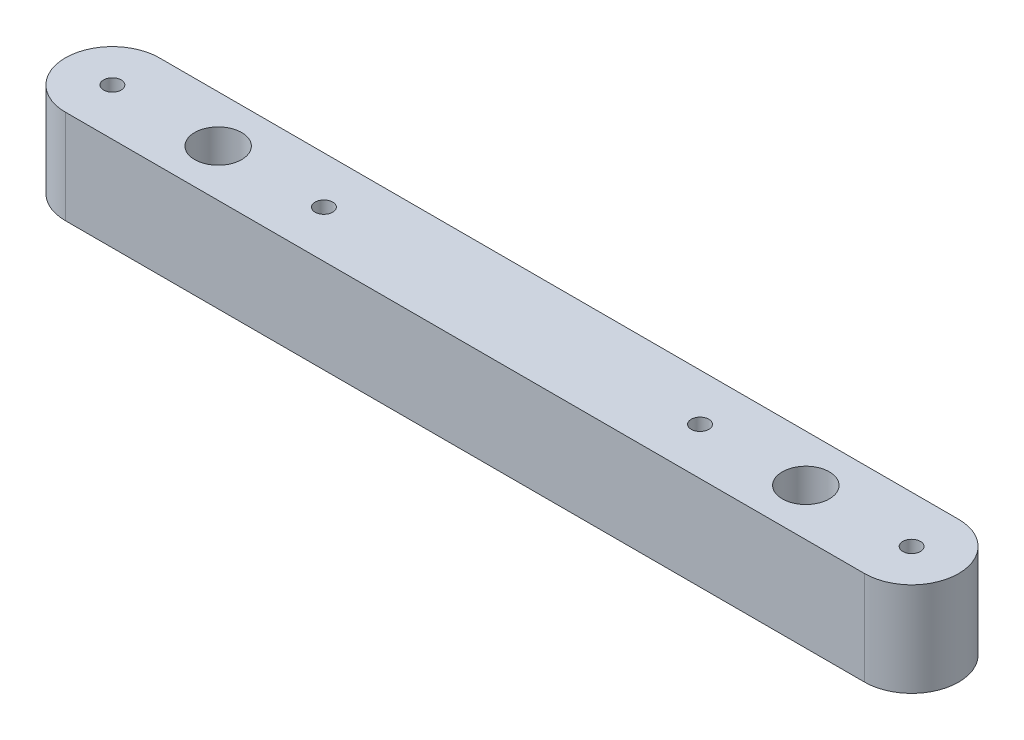
SolidWorks part; units mm, degrees
ref_plane "前基準面" through (0, 0, 0) normal (0, 0, 1) x (1, 0, 0)
ref_plane "上基準面" through (0, 0, 0) normal (0, 1, 0) x (1, 0, 0)
ref_plane "右基準面" through (0, 0, 0) normal (1, 0, 0) x (0, 0, -1)
sketch "草圖1" plane through (0, 0, 0) normal (0, 1, 0) x (1, 0, 0)
  line L0 (-25, 0) -> (25, 0) construction
  line L1 (-0.414, -4) -> (25, -4)
  line L2 (-0.414, 4) -> (25, 4)
  line L3 (34, 0) -> (-34, 0) construction
  line L4 (-34, 4) -> (-0.414, 4)
  line L5 (-34, -4) -> (-0.414, -4)
  line L6 (25, 4) -> (34, 4)
  line L7 (34, -4) -> (25, -4)
  circle A0 centre (34, 0) radius 0.75
  circle A1 centre (-34, 0) radius 0.75
  circle A2 centre (-25, 0) radius 2
  circle A3 centre (25, 0) radius 2
  arc A4 (-34, 4) -> (-34, -4) centre (-34, 0) ccw
  arc A5 (34, 4) -> (34, -4) centre (34, 0) cw
  circle A7 centre (-16, 0) radius 0.75
  circle A8 centre (16, 0) radius 0.75
  dimension "D2" = 4
  dimension "D3" = 9
  dimension "D4" = 1.5
  dimension "D1" = 50
  dimension "D5" = 8
  dimension "D11" = 9
  dimension "D12" = 9
extrude "填料-伸長1" add sketch "草圖1" along normal blind 8
